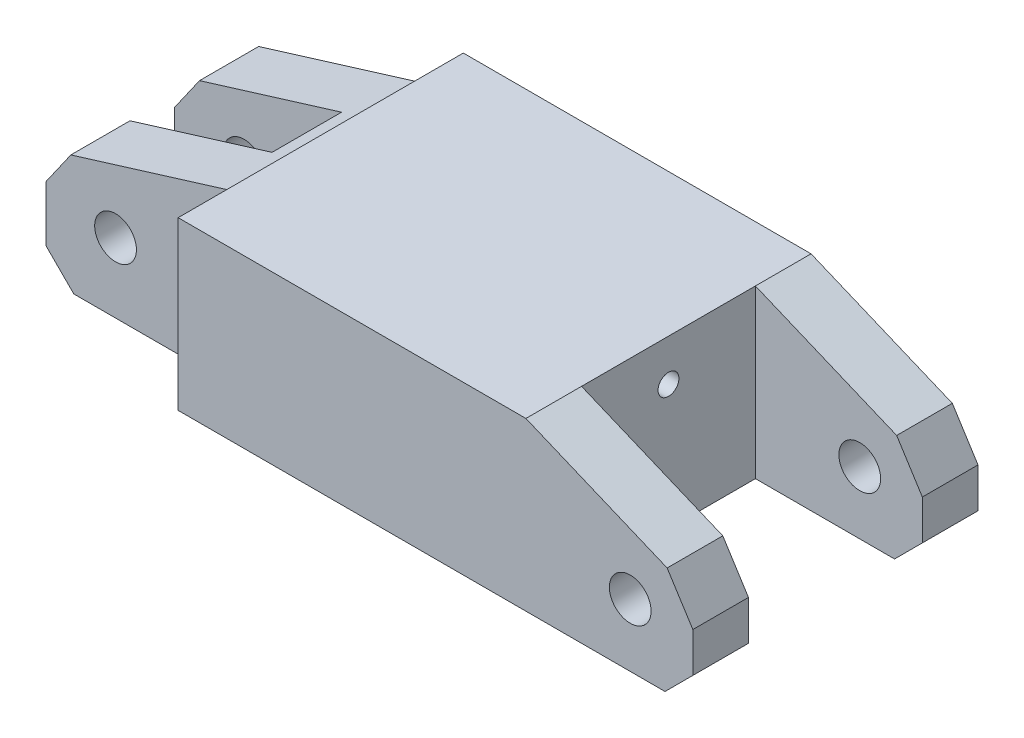
SolidWorks part; units mm, degrees
ref_plane "Спереди" through (0, 0, 0) normal (0, 0, 1) x (1, 0, 0)
ref_plane "Сверху" through (0, 0, 0) normal (0, 1, 0) x (1, 0, 0)
ref_plane "Справа" through (0, 0, 0) normal (1, 0, 0) x (0, 0, -1)
sketch "Эскиз2" plane through (0, 0, 0) normal (1, 0, 0) x (0, 0, -1)
  line L1 (-10.25, 6) -> (10.25, 6)
  line L2 (-10.25, 6) -> (-10.25, -6)
  line L3 (-10.25, -6) -> (10.25, -6)
  line L4 (10.25, 6) -> (10.25, -6)
  line L5 (-10.25, 6) -> (10.25, -6) construction
  line L6 (-10.25, -6) -> (10.25, 6) construction
  point P0 (0, 0)
extrude "Вытянуть1" add sketch "Эскиз2" along normal blind 50
sketch "Эскиз3" plane through (0, 6, 0) normal (0, 1, 0) x (1, 0, 0)
  line L0 (0, 0) -> (-9.2006, 0) construction
  line L1 (0, 10.25) -> (0, -10.25) construction
  line L2 (-12, 2.5) -> (12, 2.5)
  line L3 (-12, 2.5) -> (-12, -2.5)
  line L4 (-12, -2.5) -> (12, -2.5)
  line L5 (12, 2.5) -> (12, -2.5)
  line L6 (-12, 2.5) -> (12, -2.5) construction
  line L7 (-12, -2.5) -> (12, 2.5) construction
  point P1 (0, 0)
  dimension "D1" = 12
extrude "Вырез-Вытянуть1" cut sketch "Эскиз3" against normal through all
sketch "Эскиз5" plane through (0, 6, 0) normal (0, 1, 0) x (1, 0, 0)
  line L0 (40, 0) -> (51.6105, 0) construction
  line L1 (50, 10.25) -> (0, 10.25) construction
  line L2 (50, 10.25) -> (50, -10.25) construction
  line L3 (38, 6.25) -> (51.1226, 6.25)
  line L4 (38, 6.25) -> (38, -6.25)
  line L5 (38, -6.25) -> (51.1226, -6.25)
  line L6 (51.1226, 6.25) -> (51.1226, -6.25)
  line L7 (38, 6.25) -> (51.1226, -6.25) construction
  line L8 (38, -6.25) -> (51.1226, 6.25) construction
  point P1 (44.5613, 0)
  dimension "D1" = 12
  dimension "D2" = 4
extrude "Вырез-Вытянуть2" cut sketch "Эскиз5" against normal through all
sketch "Эскиз7" plane through (38, 0, 0) normal (1, 0, 0) x (0, 0, -1)
  line L0 (0, 6) -> (0, 3.9395) construction
  line L1 (6.25, 6) -> (-6.25, 6) construction
  circle A0 centre (0, 3) radius 0.75
  dimension "D1" = 3
extrude "Вытянуть3" cut sketch "Эскиз7" against normal through all
sketch "Эскиз10" plane through (0, 6, 0) normal (0, 1, 0) x (1, 0, 0)
  line L0 (5.6157, 0) -> (-3.5713, 0) construction
  line L1 (0, 10.25) -> (0, 2.5) construction
  line L2 (12, 2.5) -> (0, 2.5) construction
  line L3 (-6.1065, 15.4507) -> (13, 15.4507)
  line L4 (-6.1065, 15.4507) -> (-6.1065, 6.75)
  line L5 (-6.1065, 6.75) -> (13, 6.75)
  line L6 (13, 15.4507) -> (13, 6.75)
  line L7 (-6.1065, -15.4507) -> (13, -15.4507)
  line L8 (-6.1065, -15.4507) -> (-6.1065, -6.75)
  line L9 (-6.1065, -6.75) -> (13, -6.75)
  line L10 (13, -15.4507) -> (13, -6.75)
  dimension "D1" = 4.25
  dimension "D2" = 13
extrude "Вырез-Вытянуть3" cut sketch "Эскиз10" against normal through all
sketch "Эскиз11" plane through (0, 0, 6.75) normal (0, 0, 1) x (1, 0, 0)
  line L0 (0, -6) -> (0, 6) construction
  line L2 (13, -6) -> (0, -6) construction
  circle A0 centre (5, -1) radius 1.5
  dimension "D1" = 5
  dimension "D2" = 5
extrude "Вытянуть6" cut sketch "Эскиз11" against normal through all
sketch "Эскиз9" plane through (0, 0, 10.25) normal (0, 0, 1) x (1, 0, 0)
  line L0 (50, 6) -> (50, -6) construction
  line L2 (50, -6) -> (13, -6) construction
  circle A0 centre (45.5, -1.5) radius 1.5
  dimension "D1" = 4.5
  dimension "D2" = 4.5
extrude "Вытянуть5" cut sketch "Эскиз9" against normal through all
sketch "Эскиз12" plane through (12, 0, 0) normal (-1, 0, 0) x (0, 0, 1)
  circle A0 centre (-1.7914, -3.4073) radius 0.75
extrude "Вырез-Вытянуть4" cut sketch "Эскиз12" against normal blind 12
sketch "Эскиз13" plane through (0, 0, 10.25) normal (0, 0, 1) x (1, 0, 0)
  line L0 (13, 6) -> (0, 6)
  line L1 (50, 6) -> (13, 6) construction
  line L2 (0, -6) -> (0, 6) construction
  line L3 (0, 6) -> (0, 2)
  line L4 (0, 2) -> (13, 6)
  line L6 (50, 6) -> (50, 1)
  line L7 (13, 6) -> (0, 6) construction
  line L8 (50, 1) -> (38, 6)
  line L9 (38, 6) -> (50, 6)
  line L10 (50, 6) -> (50, -6) construction
  dimension "D2" = 4
  dimension "D1" = 13
  dimension "D3" = 12
extrude "Вытянуть7" cut sketch "Эскиз13" against normal through all
chamfer "Фаска5" distance 2 angle 45 4 edges at (0, -6, 4.625) (0, -6, -4.625) (50, -6, -8.25) (50, -6, 8.25)
chamfer "Фаска6" distance 2 angle 35 4 edges at (0, 2, 4.625) (0, 2, -4.625) (50, 1, -8.25) (50, 1, 8.25)
sketch "Эскиз14" plane through (38, 0, 0) normal (1, 0, 0) x (0, 0, -1)
  line L0 (-6.25, -1.1421) -> (-6.25, -4) construction
  line L1 (6.25, -6) -> (-6.25, -6) construction
  circle A0 centre (-2, -3.75) radius 0.75
  dimension "D1" = 4.25
  dimension "D2" = 2.25
extrude "Вырез-Вытянуть5" cut sketch "Эскиз14" against normal blind 6
sketch "Эскиз15" plane through (0, -6, 0) normal (0, -1, 0) x (1, 0, 0)
  line L0 (13, 10.25) -> (13, 6.75) construction
  line L1 (18, 6.25) -> (32, 6.25)
  line L2 (15, 3.25) -> (15, -3.25)
  line L3 (18, -6.25) -> (32, -6.25)
  line L4 (35, 3.25) -> (35, -3.25)
  line L5 (38, -6.25) -> (38, 6.25) construction
  line L6 (48, 10.25) -> (13, 10.25) construction
  line L7 (48, -10.25) -> (13, -10.25) construction
  arc A0 (18, 6.25) -> (15, 3.25) centre (18, 3.25) ccw
  arc A1 (35, 3.25) -> (32, 6.25) centre (32, 3.25) ccw
  arc A2 (32, -6.25) -> (35, -3.25) centre (32, -3.25) ccw
  arc A3 (15, -3.25) -> (18, -6.25) centre (18, -3.25) ccw
  dimension "D5" = 3
  dimension "D1" = 2
  dimension "D2" = 3
  dimension "D3" = 4
  dimension "D4" = 4
extrude "Вытянуть8" cut sketch "Эскиз15" against normal blind 10
sketch "Эскиз16" plane through (12, 0, 0) normal (-1, 0, 0) x (0, 0, 1)
  circle A0 centre (1.7484, 3.0009) radius 0.75
extrude "Вытянуть9" cut sketch "Эскиз16" against normal blind 5
